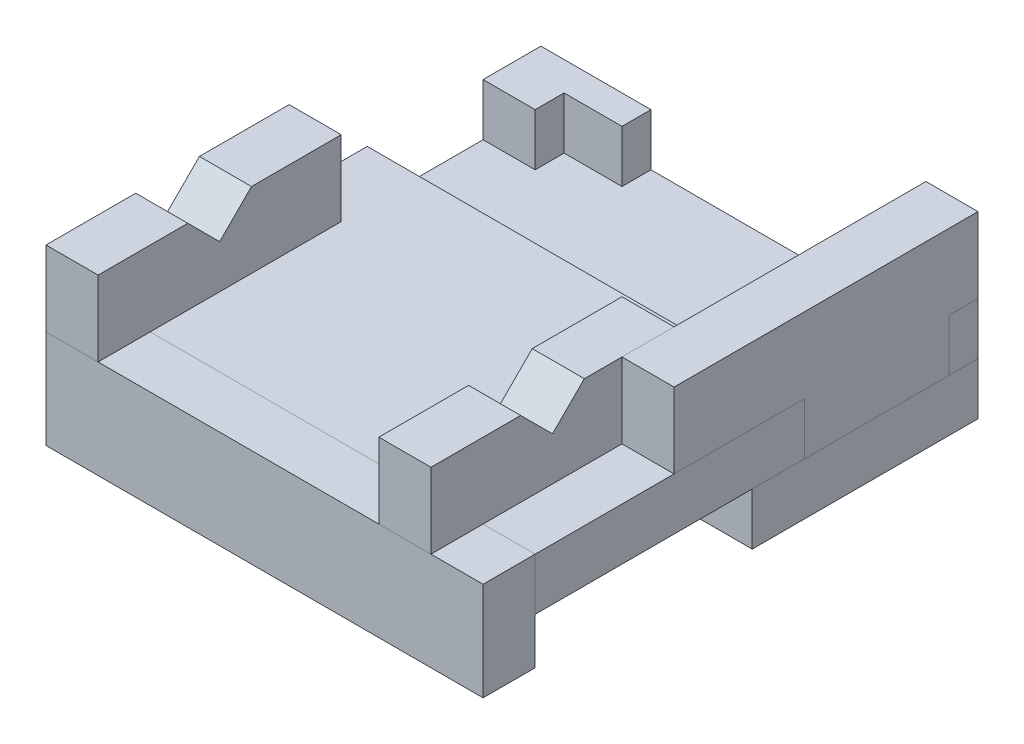
SolidWorks part; units mm, degrees
material "Pine"
ref_plane "Front Plane" through (0, 0, 0) normal (0, 0, 1) x (1, 0, 0)
ref_plane "Top Plane" through (0, 0, 0) normal (0, 1, 0) x (1, 0, 0)
ref_plane "Right Plane" through (0, 0, 0) normal (1, 0, 0) x (0, 0, -1)
sketch "Sketch1" plane through (0, 0, 0) normal (0, 1, 0) x (1, 0, 0)
  line L0 (-20.6769, 0) -> (20.6769, 0) construction
  line L1 (-53, 74) -> (98, 74)
  line L2 (-53, 74) -> (-53, -19)
  line L3 (-53, -19) -> (98, -19)
  line L4 (98, 74) -> (98, -19)
  line L5 (0, -55) -> (0, 55) construction
  dimension "D1" = 93
  dimension "D2" = 151
  dimension "D3" = 74
  dimension "D4" = 53
extrude "Boss-Extrude1" add sketch "Sketch1" along normal blind 18
ref_plane "Plane1" through (80, 0, 0) normal (1, 0, 0) x (0, 0, -1)
sketch "Sketch2" plane through (80, 0, 0) normal (1, 0, 0) x (0, 0, -1)
  line L1 (-37, 18) -> (47, 18)
  line L2 (-37, 18) -> (-37, 44)
  line L3 (-37, 44) -> (-6, 44)
  line L4 (47, 44) -> (47, 18)
  line L5 (-6, 44) -> (5, 33)
  line L6 (5, 33) -> (16, 44)
  line L7 (16, 44) -> (47, 44)
  line L9 (0, 20.6769) -> (0, -20.6769) construction
  line L11 (-19, 18) -> (74, 18) construction
  dimension "D6" = 42
  dimension "D1" = 135
  dimension "D2" = 15
  dimension "D3" = 42
  dimension "D4" = 26
  dimension "D5" = 5
extrude "Boss-Extrude2" add sketch "Sketch2" against normal blind 18 separate body
sketch "Sketch3" plane through (98, 0, 0) normal (1, 0, 0) x (0, 0, -1)
  line L0 (51.15, 0) -> (-51.15, 0) construction
  line L1 (-37, 18) -> (-19, 18)
  line L2 (-37, 18) -> (-37, -16)
  line L3 (-37, -16) -> (-19, -16)
  line L4 (-19, 18) -> (-19, -16)
  line L6 (-19, 18) -> (-19, 0) construction
  line L7 (56, 0) -> (134, 0)
  line L8 (56, 0) -> (56, -18)
  line L9 (56, -18) -> (134, -18)
  line L10 (134, 0) -> (134, -18)
  dimension "D1" = 34
  dimension "D2" = 18
  dimension "D3" = 75
  dimension "D4" = 78
  dimension "D5" = 18
  dimension "D6" = 18
extrude "Boss-Extrude3" add sketch "Sketch3" against normal up to surface (151 mm away) separate body up to face at (-53, 9, -27.5)
sketch "Sketch4" plane through (-53, 0, 0) normal (-1, 0, 0) x (0, 0, 1)
  line L7 (37, 18) -> (37, 44)
  line L8 (37, 44) -> (6, 44)
  line L9 (6, 44) -> (-5, 33)
  line L10 (-5, 33) -> (-16, 44)
  line L11 (-16, 44) -> (-47, 44)
  line L12 (-47, 44) -> (-47, 18)
  line L13 (-47, 18) -> (37, 18)
  line L14 (37, 18) -> (37, 44)
  line L15 (37, 44) -> (6, 44)
  line L16 (6, 44) -> (-5, 33)
  line L17 (-5, 33) -> (-16, 44)
  line L18 (-16, 44) -> (-47, 44)
  line L19 (-47, 44) -> (-47, 18)
  line L20 (-47, 18) -> (37, 18)
  dimension "D1" = 0
extrude "Boss-Extrude4" add sketch "Sketch4" against normal blind 18 separate body
sketch "Sketch5" plane through (98, 0, 0) normal (1, 0, 0) x (0, 0, -1)
  line L0 (134, 0) -> (56, 0) construction
  line L1 (74, 18) -> (74, 0) construction
  line L3 (124, 0) -> (74, 0)
  line L4 (74, 18) -> (74, 0)
  line L5 (124, 0) -> (124, 18)
  line L6 (134, 44) -> (134, 18)
  line L7 (134, -18) -> (134, 0) construction
  line L9 (134, 44) -> (29, 44)
  line L10 (29, 44) -> (29, 18)
  line L11 (-19, 18) -> (74, 18) construction
  line L12 (29, 18) -> (74, 18)
  line L13 (124, 18) -> (134, 18)
  line M4 (134, 0) -> (56, 0)
  dimension "D1" = 45
  dimension "D2" = 10
  dimension "D3" = 18
  dimension "D4" = 44
extrude "Boss-Extrude5" add sketch "Sketch5" against normal blind 18 separate body contours L10 L12 L4 L6 L9 M4
sketch "Sketch7" plane through (0, 0, 0) normal (0, 1, 0) x (1, 0, 0)
  line L0 (-35, 114) -> (-35, 124)
  line L1 (-35, 124) -> (-15, 124)
  line L2 (98, 74) -> (-53, 74) construction
  line L3 (80, -9.9) -> (80, 9.9) construction
  line L4 (-35, 114) -> (-53, 114)
  line L6 (-53, 114) -> (-53, 134)
  line L7 (-53, 134) -> (-15, 134)
  line L8 (-15, 134) -> (-15, 124)
  line L9 (98, 134) -> (98, 56) construction
  line L10 (98, 124) -> (68, 124)
  line L11 (98, 124) -> (98, 134)
  line L12 (98, 134) -> (68, 134)
  line L13 (68, 124) -> (68, 134)
  dimension "D1" = 50
  dimension "D2" = 115
  dimension "D3" = 18
  dimension "D4" = 40
  dimension "D5" = 10
  dimension "D6" = 30
  dimension "D7" = 10
  dimension "D8" = 50
  dimension "D9" = 20
extrude "Boss-Extrude6" add sketch "Sketch7" along normal blind 18 separate body
